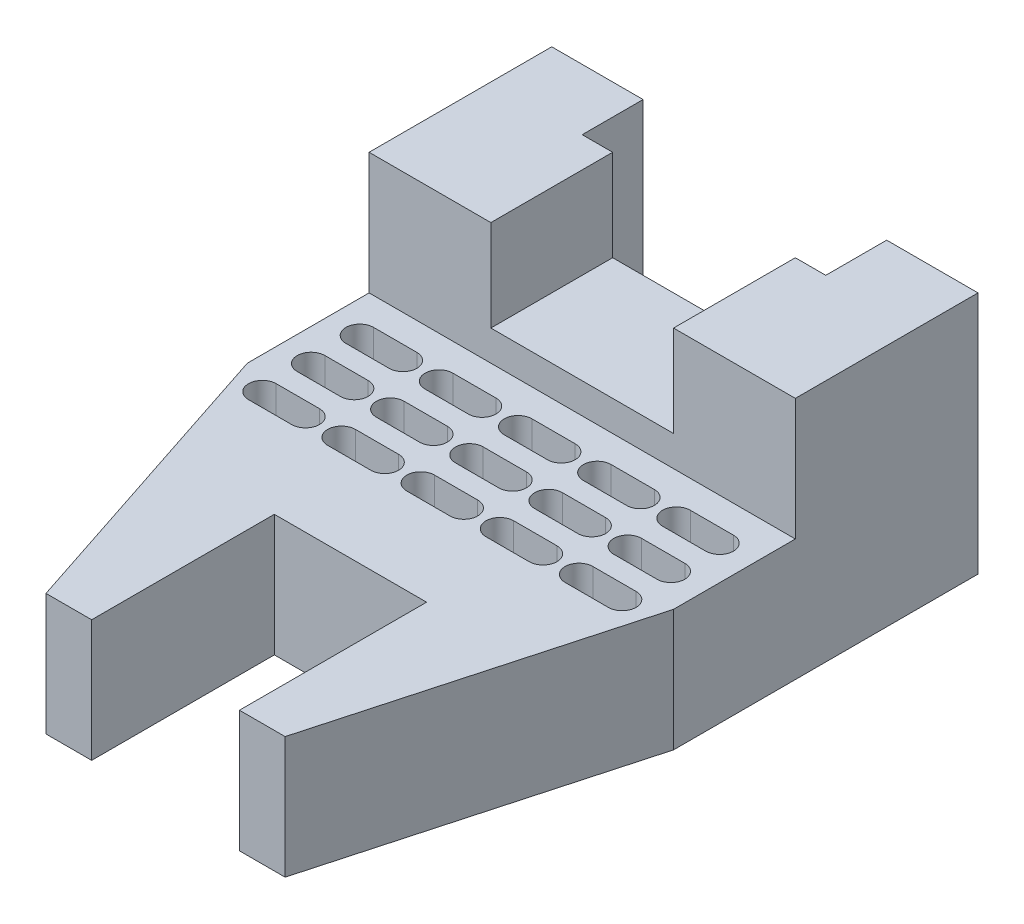
SolidWorks part; units mm, degrees
ref_plane "Front Plane" through (0, 0, 0) normal (0, 0, 1) x (1, 0, 0)
ref_plane "Top Plane" through (0, 0, 0) normal (0, 1, 0) x (1, 0, 0)
ref_plane "Right Plane" through (0, 0, 0) normal (1, 0, 0) x (0, 0, -1)
sketch "Sketch2" plane through (0, 0, 0) normal (0, 0, 1) x (1, 0, 0)
  line L1 (0, 0) -> (70, 0)
  line L2 (0, 0) -> (0, 40)
  line L3 (0, 40) -> (70, 40)
  line L4 (70, 0) -> (70, 40)
  dimension "D1" = 70
  dimension "D2" = 40
extrude "Boss-Extrude1" add sketch "Sketch2" along normal blind 50
sketch "Sketch3" plane through (0, 40, 0) normal (0, 1, 0) x (1, 0, 0)
  line L0 (70, 0) -> (0, 0) construction
  line L1 (15, 0) -> (55, 0)
  line L2 (15, 0) -> (15, -10)
  line L3 (15, -10) -> (55, -10)
  line L4 (55, 0) -> (55, -10)
  dimension "D1" = 40
  dimension "D2" = 10
  dimension "D3" = 15
extrude "Cut-Extrude1" cut sketch "Sketch3" against normal blind 40
sketch "Sketch4" plane through (0, 40, 0) normal (0, 1, 0) x (1, 0, 0)
  line L0 (15, -10) -> (55, -10) construction
  line L1 (20, -10) -> (50, -10)
  line L2 (20, -10) -> (20, -50)
  line L3 (20, -50) -> (50, -50)
  line L4 (50, -10) -> (50, -50)
  line L5 (70, -50) -> (0, -50) construction
  line L6 (15, 0) -> (15, -10) construction
  dimension "D1" = 30
  dimension "D2" = 5
extrude "Cut-Extrude2" cut sketch "Sketch4" against normal blind 15
sketch "Sketch5" plane through (0, 40, 0) normal (0, 1, 0) x (1, 0, 0)
  line L0 (70, -50) -> (70, 0) construction
  line L1 (0, -50) -> (70, -50)
  line L2 (0, -50) -> (0, -30)
  line L3 (0, -30) -> (70, -30)
  line L4 (70, -50) -> (70, -30)
  dimension "D1" = 20
extrude "Cut-Extrude3" cut sketch "Sketch5" against normal blind 20
sketch "Sketch6" plane through (0, 0, 0) normal (0, -1, 0) x (1, 0, 0)
  line L0 (0, 50) -> (16.2098, 99.2688)
  line L1 (0, 50) -> (70, 50)
  line L2 (56.2098, 100) -> (70, 50)
  line L3 (16.2098, 99.2688) -> (23.7098, 99.2688)
  line L4 (23.7098, 99.2688) -> (23.7098, 69.2688)
  line L5 (23.7098, 69.2688) -> (48.7098, 69.2688)
  line L6 (48.7098, 69.2688) -> (48.7098, 100)
  line L7 (48.7098, 100) -> (56.2098, 100)
  dimension "D1" = 25
  dimension "D2" = 7.5
  dimension "D3" = 30
  dimension "D4" = 50
extrude "Boss-Extrude2" add sketch "Sketch6" against normal blind 20
sketch "Sketch7" plane through (0, 20, 0) normal (0, 1, 0) x (1, 0, 0)
  line L0 (5.2844, -36.8109) -> (12.3786, -36.8109) construction
  line L1 (5.2844, -34.5354) -> (12.3786, -34.5354)
  line L2 (5.2844, -39.0865) -> (12.3786, -39.0865)
  line L3 (18.2844, -36.8109) -> (25.3786, -36.8109) construction
  line L4 (18.2844, -34.5354) -> (25.3786, -34.5354)
  line L5 (18.2844, -39.0865) -> (25.3786, -39.0865)
  line L6 (31.2844, -36.8109) -> (38.3786, -36.8109) construction
  line L7 (31.2844, -34.5354) -> (38.3786, -34.5354)
  line L8 (31.2844, -39.0865) -> (38.3786, -39.0865)
  line L9 (44.2844, -36.8109) -> (51.3786, -36.8109) construction
  line L10 (44.2844, -34.5354) -> (51.3786, -34.5354)
  line L11 (44.2844, -39.0865) -> (51.3786, -39.0865)
  line L12 (57.2844, -36.8109) -> (64.3786, -36.8109) construction
  line L13 (57.2844, -34.5354) -> (64.3786, -34.5354)
  line L14 (57.2844, -39.0865) -> (64.3786, -39.0865)
  line L15 (18.2844, -44.8109) -> (25.3786, -44.8109) construction
  line L16 (18.2844, -42.5354) -> (25.3786, -42.5354)
  line L17 (18.2844, -47.0865) -> (25.3786, -47.0865)
  line L18 (31.2844, -44.8109) -> (38.3786, -44.8109) construction
  line L19 (31.2844, -42.5354) -> (38.3786, -42.5354)
  line L20 (31.2844, -47.0865) -> (38.3786, -47.0865)
  line L21 (44.2844, -44.8109) -> (51.3786, -44.8109) construction
  line L22 (44.2844, -42.5354) -> (51.3786, -42.5354)
  line L23 (44.2844, -47.0865) -> (51.3786, -47.0865)
  line L24 (57.2844, -44.8109) -> (64.3786, -44.8109) construction
  line L25 (57.2844, -42.5354) -> (64.3786, -42.5354)
  line L26 (57.2844, -47.0865) -> (64.3786, -47.0865)
  line L27 (18.2844, -52.8109) -> (25.3786, -52.8109) construction
  line L28 (18.2844, -50.5354) -> (25.3786, -50.5354)
  line L29 (18.2844, -55.0865) -> (25.3786, -55.0865)
  line L30 (31.2844, -52.8109) -> (38.3786, -52.8109) construction
  line L31 (31.2844, -50.5354) -> (38.3786, -50.5354)
  line L32 (31.2844, -55.0865) -> (38.3786, -55.0865)
  line L33 (44.2844, -52.8109) -> (51.3786, -52.8109) construction
  line L34 (44.2844, -50.5354) -> (51.3786, -50.5354)
  line L35 (44.2844, -55.0865) -> (51.3786, -55.0865)
  line L36 (57.2844, -52.8109) -> (64.3786, -52.8109) construction
  line L37 (57.2844, -50.5354) -> (64.3786, -50.5354)
  line L38 (57.2844, -55.0865) -> (64.3786, -55.0865)
  line L39 (5.2844, -44.8109) -> (12.3786, -44.8109) construction
  line L40 (5.2844, -42.5354) -> (12.3786, -42.5354)
  line L41 (5.2844, -47.0865) -> (12.3786, -47.0865)
  line L42 (5.2844, -52.8109) -> (12.3786, -52.8109) construction
  line L43 (5.2844, -50.5354) -> (12.3786, -50.5354)
  line L44 (5.2844, -55.0865) -> (12.3786, -55.0865)
  arc A0 (5.2844, -34.5354) -> (5.2844, -39.0865) centre (5.2844, -36.8109) ccw
  arc A1 (12.3786, -39.0865) -> (12.3786, -34.5354) centre (12.3786, -36.8109) ccw
  arc A2 (18.2844, -34.5354) -> (18.2844, -39.0865) centre (18.2844, -36.8109) ccw
  arc A3 (25.3786, -39.0865) -> (25.3786, -34.5354) centre (25.3786, -36.8109) ccw
  arc A4 (31.2844, -34.5354) -> (31.2844, -39.0865) centre (31.2844, -36.8109) ccw
  arc A5 (38.3786, -39.0865) -> (38.3786, -34.5354) centre (38.3786, -36.8109) ccw
  arc A6 (44.2844, -34.5354) -> (44.2844, -39.0865) centre (44.2844, -36.8109) ccw
  arc A7 (51.3786, -39.0865) -> (51.3786, -34.5354) centre (51.3786, -36.8109) ccw
  arc A8 (57.2844, -34.5354) -> (57.2844, -39.0865) centre (57.2844, -36.8109) ccw
  arc A9 (64.3786, -39.0865) -> (64.3786, -34.5354) centre (64.3786, -36.8109) ccw
  arc A10 (18.2844, -42.5354) -> (18.2844, -47.0865) centre (18.2844, -44.8109) ccw
  arc A11 (25.3786, -47.0865) -> (25.3786, -42.5354) centre (25.3786, -44.8109) ccw
  arc A12 (31.2844, -42.5354) -> (31.2844, -47.0865) centre (31.2844, -44.8109) ccw
  arc A13 (38.3786, -47.0865) -> (38.3786, -42.5354) centre (38.3786, -44.8109) ccw
  arc A14 (44.2844, -42.5354) -> (44.2844, -47.0865) centre (44.2844, -44.8109) ccw
  arc A15 (51.3786, -47.0865) -> (51.3786, -42.5354) centre (51.3786, -44.8109) ccw
  arc A16 (57.2844, -42.5354) -> (57.2844, -47.0865) centre (57.2844, -44.8109) ccw
  arc A17 (64.3786, -47.0865) -> (64.3786, -42.5354) centre (64.3786, -44.8109) ccw
  arc A18 (18.2844, -50.5354) -> (18.2844, -55.0865) centre (18.2844, -52.8109) ccw
  arc A19 (25.3786, -55.0865) -> (25.3786, -50.5354) centre (25.3786, -52.8109) ccw
  arc A20 (31.2844, -50.5354) -> (31.2844, -55.0865) centre (31.2844, -52.8109) ccw
  arc A21 (38.3786, -55.0865) -> (38.3786, -50.5354) centre (38.3786, -52.8109) ccw
  arc A22 (44.2844, -50.5354) -> (44.2844, -55.0865) centre (44.2844, -52.8109) ccw
  arc A23 (51.3786, -55.0865) -> (51.3786, -50.5354) centre (51.3786, -52.8109) ccw
  arc A24 (57.2844, -50.5354) -> (57.2844, -55.0865) centre (57.2844, -52.8109) ccw
  arc A25 (64.3786, -55.0865) -> (64.3786, -50.5354) centre (64.3786, -52.8109) ccw
  arc A26 (5.2844, -42.5354) -> (5.2844, -47.0865) centre (5.2844, -44.8109) ccw
  arc A27 (12.3786, -47.0865) -> (12.3786, -42.5354) centre (12.3786, -44.8109) ccw
  arc A28 (5.2844, -50.5354) -> (5.2844, -55.0865) centre (5.2844, -52.8109) ccw
  arc A29 (12.3786, -55.0865) -> (12.3786, -50.5354) centre (12.3786, -52.8109) ccw
  point P2 (8.8315, -36.8109)
  point P11 (21.8315, -36.8109)
  point P18 (34.8315, -36.8109)
  point P25 (47.8315, -36.8109)
  point P32 (60.8315, -36.8109)
  point P39 (21.8315, -44.8109)
  point P46 (34.8315, -44.8109)
  point P53 (47.8315, -44.8109)
  point P60 (60.8315, -44.8109)
  point P67 (21.8315, -52.8109)
  point P74 (34.8315, -52.8109)
  point P81 (47.8315, -52.8109)
  point P88 (60.8315, -52.8109)
  point P95 (8.8315, -44.8109)
  point P102 (8.8315, -52.8109)
  dimension "D1" = 5
  dimension "D2" = 3
extrude "Cut-Extrude4" cut sketch "Sketch7" against normal through all
sketch3d "3DSketch1"
  line L0 (70, 0, 50) -> (70, 20, 50) construction
  line L1 (70, 0, 50) -> (70, 20, 50)
